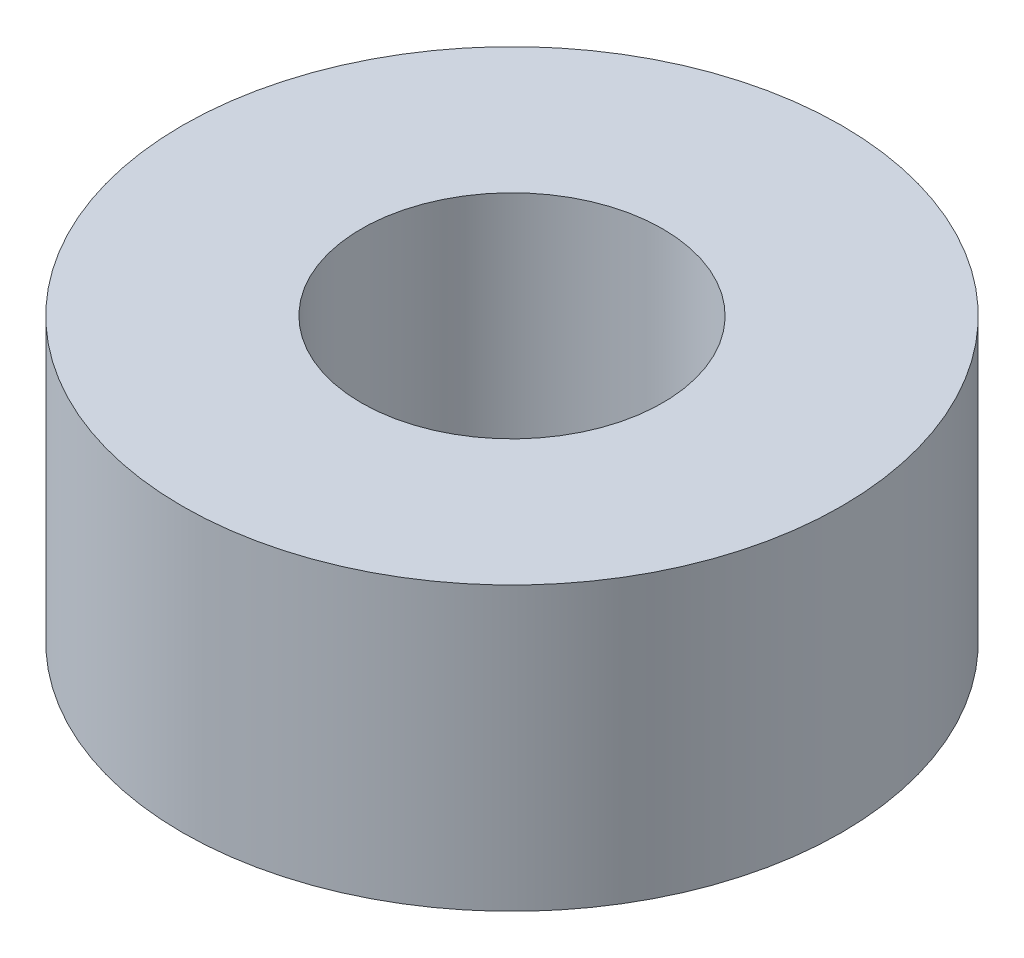
SolidWorks part; units mm, degrees
material "ABS"
ref_plane "前视基准面" through (0, 0, 0) normal (0, 0, 1) x (1, 0, 0)
ref_plane "上视基准面" through (0, 0, 0) normal (0, 1, 0) x (1, 0, 0)
ref_plane "右视基准面" through (0, 0, 0) normal (1, 0, 0) x (0, 0, -1)
sketch "草图1" plane through (0, 0, 0) normal (0, 1, 0) x (1, 0, 0)
  circle A0 centre (0, 0) radius 3.5
  circle A1 centre (0, 0) radius 1.6
  dimension "D1" = 7
  dimension "D2" = 3.2
extrude "凸台-拉伸1" add sketch "草图1" along normal blind 3
